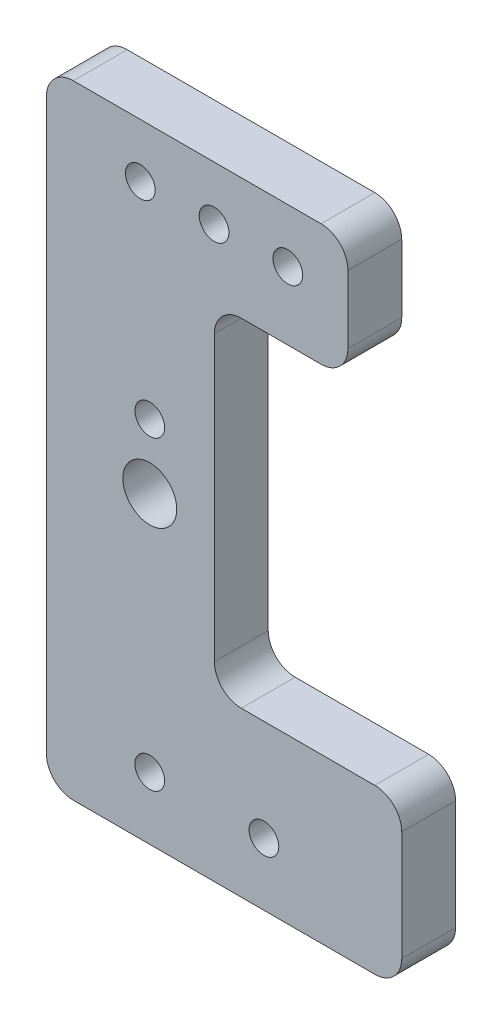
SolidWorks part; units mm, degrees
ref_plane "Front Plane" through (0, 0, 0) normal (0, 0, 1) x (1, 0, 0)
ref_plane "Top Plane" through (0, 0, 0) normal (0, 1, 0) x (1, 0, 0)
ref_plane "Right Plane" through (0, 0, 0) normal (1, 0, 0) x (0, 0, -1)
sketch "Sketch1" plane through (0, 0, 0) normal (0, 0, 1) x (1, 0, 0)
  line L0 (-16.5989, 7.31) -> (12.6111, 7.31)
  line L1 (15.7861, 4.135) -> (15.7861, -3.8645)
  line L2 (12.6111, -7.0395) -> (3.2131, -7.0395)
  line L3 (0.0381, -10.2145) -> (0.0381, -43.7039)
  line L4 (3.2131, -46.8789) -> (18.9611, -46.8789)
  line L5 (22.1361, -50.0539) -> (22.1361, -63.0079)
  line L6 (18.9611, -66.1829) -> (-16.5989, -66.1829)
  line L7 (-19.7739, -63.0079) -> (-19.7739, 4.135)
  line L8 (-8.6995, 0.96) -> (0, 0) construction
  line L9 (0, 0) -> (8.6995, 0.96) construction
  line L10 (-8.6995, 0.96) -> (8.6995, 0.96) construction
  line L12 (22.7284, -23.5253) -> (67.2575, -32.0311) construction
  line L13 (-7.5819, -22.7489) -> (-7.5819, -58.8169) construction
  line L14 (-7.5819, -58.8169) -> (5.8801, -58.8169) construction
  circle A1 centre (-8.6995, 0.96) radius 1.7526
  circle A2 centre (8.6995, 0.96) radius 1.7526
  circle A3 centre (-7.5819, -22.7489) radius 1.7526
  circle A4 centre (-7.5819, -30.3689) radius 3.175
  circle A5 centre (-7.5819, -58.8169) radius 1.7526
  circle A6 centre (5.8801, -58.8169) radius 1.7526
  arc A7 (-19.7739, 4.135) -> (-16.5989, 7.31) centre (-16.5989, 4.135) cw
  arc A8 (-19.7739, -63.0079) -> (-16.5989, -66.1829) centre (-16.5989, -63.0079) ccw
  arc A9 (18.9611, -66.1829) -> (22.1361, -63.0079) centre (18.9611, -63.0079) ccw
  arc A10 (22.1361, -50.0539) -> (18.9611, -46.8789) centre (18.9611, -50.0539) ccw
  arc A11 (3.2131, -46.8789) -> (0.0381, -43.7039) centre (3.2131, -43.7039) cw
  arc A12 (15.7861, 4.135) -> (12.6111, 7.31) centre (12.6111, 4.135) ccw
  arc A13 (15.7861, -3.8645) -> (12.6111, -7.0395) centre (12.6111, -3.8645) cw
  arc A14 (3.2131, -7.0395) -> (0.0381, -10.2145) centre (3.2131, -10.2145) ccw
  circle A15 centre (0, 0.96) radius 1.7526
  point P27 (-19.7739, 7.31)
  point P38 (15.7861, 7.31)
  dimension "D13" = 3.5052
  dimension "D2" = 6.35
  dimension "D3" = 3.175
  dimension "D5" = 3.175
  dimension "D4" = 35.56
  dimension "D6" = 17.399
  dimension "D7" = 11.0744
  dimension "D8" = 39.8395
  dimension "D9" = 13.462
  dimension "D10" = 16.256
  dimension "D11" = 35.814
  dimension "D12" = 7.62
  dimension "D14" = 14.3495
  dimension "D15" = 19.304
  dimension "D16" = 7.31
  dimension "D17" = 19.812
  dimension "D18" = 41.91
  dimension "D19" = 7.366
  dimension "D20" = 6.35
extrude "Boss-Extrude1" add sketch "Sketch1" along normal mid plane 6.35
